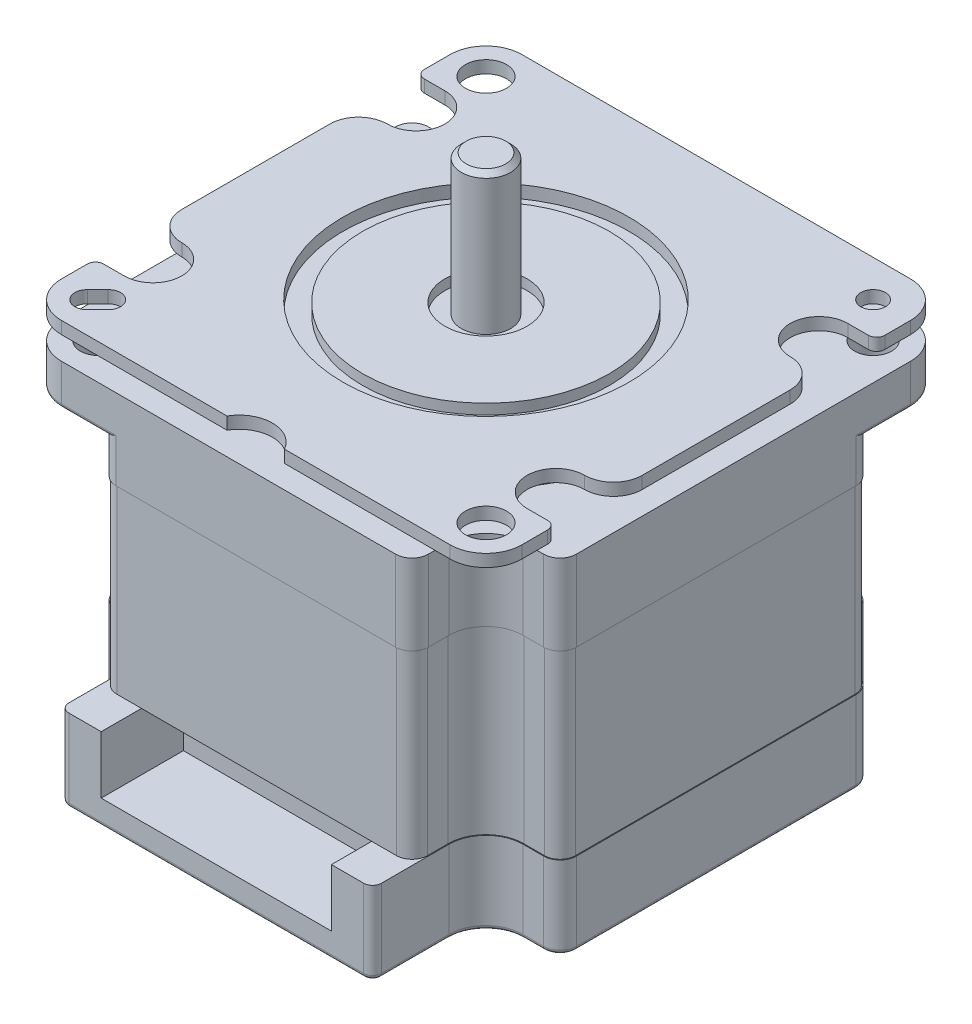
SolidWorks part; units mm, degrees
ref_plane "Front Plane" through (0, 0, 0) normal (0, 0, 1) x (1, 0, 0)
ref_plane "Top Plane" through (0, 0, 0) normal (0, 1, 0) x (1, 0, 0)
ref_plane "Right Plane" through (0, 0, 0) normal (1, 0, 0) x (0, 0, -1)
sketch "Sketch1" plane through (0, 0, 0) normal (0, 1, 0) x (1, 0, 0)
  line L0 (-24.2471, -24.2471) -> (-22.9743, -22.9743) construction
  line L1 (-23.6365, -28) -> (-3.5, -28)
  line L2 (-28, -23.6365) -> (-28, -20.5)
  line L3 (-23.6365, 28) -> (23.6365, 28)
  line L4 (28, -23.6365) -> (28, -20.5)
  line L5 (-26.722, -26.722) -> (26.722, 26.722) construction
  line L6 (-28, 28) -> (28, -28) construction
  line L7 (-25.3077, -23.1864) -> (-24.035, -21.9136)
  line L8 (-23.1864, -25.3077) -> (-21.9136, -24.035)
  line L9 (0, 0) -> (28, 0) construction
  line L10 (24.5002, 19.5) -> (27, 19.5)
  line L11 (24.5002, -19.5) -> (27, -19.5)
  line L12 (28, 20.5) -> (28, 23.6365)
  line L13 (28, -9.0002) -> (28, 9.0002)
  line L14 (0, 0) -> (0, 28) construction
  line L15 (-24.5002, -19.5) -> (-27, -19.5)
  line L16 (-24.5002, 19.5) -> (-27, 19.5)
  line L17 (-28, 20.5) -> (-28, 23.6365)
  line L18 (-28, -9.0002) -> (-28, 9.0002)
  line L19 (0, -28) -> (0, -26) construction
  line L21 (3.5, -28) -> (23.6365, -28)
  circle A0 centre (-23.5113, 23.5113) radius 2.5
  circle A1 centre (23.5113, -23.5113) radius 2.5
  arc A2 (-28, -23.6365) -> (-23.6365, -28) centre (-23.6365, -23.6365) ccw
  arc A3 (23.6365, -28) -> (28, -23.6365) centre (23.6365, -23.6365) ccw
  arc A4 (28, 23.6365) -> (23.6365, 28) centre (23.6365, 23.6365) ccw
  arc A5 (-23.6365, 28) -> (-28, 23.6365) centre (-23.6365, 23.6365) ccw
  circle A6 centre (23.54, 23.54) radius 1.5
  arc A7 (-25.3077, -23.1864) -> (-23.1864, -25.3077) centre (-24.2471, -24.2471) ccw
  arc A8 (-21.9136, -24.035) -> (-24.035, -21.9136) centre (-22.9743, -22.9743) ccw
  circle A9 centre (0, 0) radius 17.4
  arc A10 (24.5002, 19.5) -> (24.5002, 12.5) centre (24.5002, 16) ccw
  arc A11 (27, 19.5) -> (28, 20.5) centre (27, 20.5) ccw
  arc A12 (24.5002, 12.5) -> (28, 9.0002) centre (24.5002, 9.0002) cw
  arc A13 (24.5002, -12.5) -> (28, -9.0002) centre (24.5002, -9.0002) ccw
  arc A14 (24.5002, -19.5) -> (24.5002, -12.5) centre (24.5002, -16) cw
  arc A15 (27, -19.5) -> (28, -20.5) centre (27, -20.5) cw
  arc A16 (-27, -19.5) -> (-28, -20.5) centre (-27, -20.5) ccw
  arc A17 (-24.5002, -19.5) -> (-24.5002, -12.5) centre (-24.5002, -16) ccw
  arc A18 (-24.5002, -12.5) -> (-28, -9.0002) centre (-24.5002, -9.0002) cw
  arc A19 (-24.5002, 12.5) -> (-28, 9.0002) centre (-24.5002, 9.0002) ccw
  arc A20 (-24.5002, 19.5) -> (-24.5002, 12.5) centre (-24.5002, 16) cw
  arc A21 (-27, 19.5) -> (-28, 20.5) centre (-27, 20.5) cw
  arc A22 (-3.5, -28) -> (3.5, -28) centre (0, -30.017) cw
  point P0 (0, 0)
  point P26 (-23.6107, -23.6107)
  point P36 (28, 19.5)
  point P70 (3.5, -28)
  dimension "D2" = 5
  dimension "D3" = 66.5
  dimension "D4" = 4.3635
  dimension "D5" = 3
  dimension "D6" = 4.5
  dimension "D7" = 1.5
  dimension "D8" = 1.8
  dimension "D9" = 34.8
  dimension "D10" = 1
  dimension "D11" = 2
  dimension "D1" = 3.5
  dimension "D12" = 3.5
extrude "Boss-Extrude1" add sketch "Sketch1" along normal blind 1.5
ref_plane "Plane1" through (0, -2.8, 0) normal (0, -1, 0) x (-1, 0, 0)
sketch "Sketch2" plane through (0, -2.8, 0) normal (0, -1, 0) x (-1, 0, 0)
  line L0 (19, 26) -> (19, 23.5)
  line L1 (23.6365, -28) -> (-17, -28)
  line L2 (28, -23.6365) -> (28, 17)
  line L3 (17, 28) -> (-23.6365, 28)
  line L4 (-28, -17) -> (-28, 23.6365)
  line L5 (26.722, -26.722) -> (-26.722, 26.722) construction
  line L6 (20.318, 20.318) -> (-20.318, -20.318) construction
  line L7 (23.5, 19) -> (26, 19)
  line L8 (-19, -23.5) -> (-19, -26)
  line L9 (-26, -19) -> (-23.5, -19)
  arc A0 (-23.6365, 28) -> (-28, 23.6365) centre (-23.6365, 23.6365) ccw construction
  arc A1 (-23.6365, 28) -> (-28, 23.6365) centre (-23.6365, 23.6365) ccw
  arc A2 (23.5, 19) -> (19, 23.5) centre (23.5, 23.5) cw
  arc A3 (28, 17) -> (26, 19) centre (26, 17) ccw
  arc A4 (19, 26) -> (17, 28) centre (17, 26) ccw
  arc A5 (28, -23.6365) -> (23.6365, -28) centre (23.6365, -23.6365) cw
  arc A6 (-17, -28) -> (-19, -26) centre (-17, -26) cw
  arc A7 (-19, -23.5) -> (-23.5, -19) centre (-23.5, -23.5) ccw
  arc A8 (-26, -19) -> (-28, -17) centre (-26, -17) cw
  circle A9 centre (-23.54, 23.54) radius 1.5 construction
  circle A10 centre (-23.54, 23.54) radius 1.5 construction
  circle A11 centre (-23.54, 23.54) radius 2.25
  circle A12 centre (23.54, -23.54) radius 2.25
  point P0 (0, 0)
  dimension "D2" = 4.3635
  dimension "D4" = 4.5
  dimension "D5" = 2
  dimension "D7" = 4.5
  dimension "D1" = 9
  dimension "D3" = 9
extrude "Boss-Extrude2" add sketch "Sketch2" along normal blind 5 separate body
sketch "Sketch3" plane through (0, -7.8, 0) normal (0, -1, 0) x (1, 0, 0)
  line L0 (0, 0) -> (-28, 0) construction
  line L1 (-28, 0) -> (0, 0) construction
  line L2 (0, 0) -> (0, -28) construction
  line L3 (19, -23.5) -> (19, -26)
  line L4 (26, -19) -> (23.5, -19)
  line L5 (-19, 23.5) -> (-19, 26)
  line L6 (-26, 19) -> (-23.5, 19)
  line L8 (-26, -19) -> (-23.5, -19)
  line L9 (-19, -23.5) -> (-19, -26)
  line L10 (-17, -28) -> (23.6365, -28)
  line L11 (28, -23.6365) -> (28, 17)
  line L12 (26, 19) -> (23.5, 19)
  line L13 (19, 23.5) -> (19, 26)
  line L14 (17, 28) -> (-23.6365, 28)
  line L15 (-28, 23.6365) -> (-28, -17)
  line L16 (-26, -19) -> (-23.5, -19)
  line L17 (-19, -23.5) -> (-19, -26)
  line L18 (-17, -28) -> (23.6365, -28)
  line L19 (28, -23.6365) -> (28, 17)
  line L20 (26, 19) -> (23.5, 19)
  line L21 (19, 23.5) -> (19, 26)
  line L22 (17, 28) -> (-23.6365, 28)
  line L23 (-28, 23.6365) -> (-28, -17)
  arc A0 (19, -26) -> (17, -28) centre (17, -26) cw
  arc A1 (19, -23.5) -> (23.5, -19) centre (23.5, -23.5) cw
  arc A2 (28, -17) -> (26, -19) centre (26, -17) cw
  arc A3 (-19, 26) -> (-17, 28) centre (-17, 26) cw
  arc A4 (-19, 23.5) -> (-23.5, 19) centre (-23.5, 23.5) cw
  arc A5 (-28, 17) -> (-26, 19) centre (-26, 17) cw
  arc A8 (-28, -17) -> (-26, -19) centre (-26, -17) ccw
  arc A9 (-19, -23.5) -> (-23.5, -19) centre (-23.5, -23.5) ccw
  arc A10 (-19, -26) -> (-17, -28) centre (-17, -26) ccw
  arc A11 (23.6365, -28) -> (28, -23.6365) centre (23.6365, -23.6365) ccw
  arc A12 (28, 17) -> (26, 19) centre (26, 17) ccw
  arc A13 (19, 23.5) -> (23.5, 19) centre (23.5, 23.5) ccw
  arc A14 (19, 26) -> (17, 28) centre (17, 26) ccw
  arc A15 (-23.6365, 28) -> (-28, 23.6365) centre (-23.6365, 23.6365) ccw
  arc A16 (-28, -17) -> (-26, -19) centre (-26, -17) ccw
  arc A17 (-19, -23.5) -> (-23.5, -19) centre (-23.5, -23.5) ccw
  arc A18 (-19, -26) -> (-17, -28) centre (-17, -26) ccw
  arc A19 (23.6365, -28) -> (28, -23.6365) centre (23.6365, -23.6365) ccw
  arc A20 (28, 17) -> (26, 19) centre (26, 17) ccw
  arc A21 (19, 23.5) -> (23.5, 19) centre (23.5, 23.5) ccw
  arc A22 (19, 26) -> (17, 28) centre (17, 26) ccw
  arc A23 (-23.6365, 28) -> (-28, 23.6365) centre (-23.6365, 23.6365) ccw
  arc M18 (-28, -17) -> (-26, -19) centre (-26, -17) ccw
  line M19 (-26, -19) -> (-23.5, -19)
  arc M20 (-23.5, -19) -> (-19, -23.5) centre (-23.5, -23.5) cw
  line M21 (-19, -23.5) -> (-19, -26)
  arc M22 (-19, -26) -> (-17, -28) centre (-17, -26) ccw
  line M23 (-17, -28) -> (23.6365, -28)
  arc M26 (28, 17) -> (26, 19) centre (26, 17) ccw
  line M27 (26, 19) -> (23.5, 19)
  arc M28 (23.5, 19) -> (19, 23.5) centre (23.5, 23.5) cw
  line M29 (19, 23.5) -> (19, 26)
  arc M30 (19, 26) -> (17, 28) centre (17, 26) ccw
  line M31 (17, 28) -> (-23.6365, 28)
  dimension "D1" = 0
extrude "Boss-Extrude3" add sketch "Sketch3" along normal blind 4.8 contours A5 L23 A0 L3 A1 L4 A2 L19 A3 L5 A4 L6 M18 M19 M20 M21 M22 M23 M26 M27 M28 M29 M30 M31
sketch "Sketch4" plane through (0, -12.6, 0) normal (0, -1, 0) x (1, 0, 0)
  line L0 (27.9, -17) -> (27.9, 17)
  line L1 (26, 18.9) -> (23.5, 18.9)
  line L2 (18.9, 23.5) -> (18.9, 26)
  line L3 (17, 27.9) -> (-17, 27.9)
  line L4 (-18.9, 26) -> (-18.9, 23.5)
  line L5 (-23.5, 18.9) -> (-26, 18.9)
  line L6 (-27.9, 17) -> (-27.9, -17)
  line L7 (-26, -18.9) -> (-23.5, -18.9)
  line L8 (-18.9, -23.5) -> (-18.9, -26)
  line L9 (-17, -27.9) -> (17, -27.9)
  line L10 (18.9, -26) -> (18.9, -23.5)
  line L11 (23.5, -18.9) -> (26, -18.9)
  line L12 (-28, 17) -> (-28, -17)
  line L13 (-26, -19) -> (-23.5, -19)
  line L14 (-19, -23.5) -> (-19, -26)
  line L15 (-17, -28) -> (17, -28)
  line L16 (19, -26) -> (19, -23.5)
  line L17 (23.5, -19) -> (26, -19)
  line L18 (28, -17) -> (28, 17)
  line L19 (26, 19) -> (23.5, 19)
  line L20 (19, 23.5) -> (19, 26)
  line L21 (17, 28) -> (-17, 28)
  line L22 (-19, 26) -> (-19, 23.5)
  line L23 (-23.5, 19) -> (-26, 19)
  line L24 (-28, 17) -> (-28, -17)
  line L25 (-26, -19) -> (-23.5, -19)
  line L26 (-19, -23.5) -> (-19, -26)
  line L27 (-17, -28) -> (17, -28)
  line L28 (19, -26) -> (19, -23.5)
  line L29 (23.5, -19) -> (26, -19)
  line L30 (28, -17) -> (28, 17)
  line L31 (26, 19) -> (23.5, 19)
  line L32 (19, 23.5) -> (19, 26)
  line L33 (17, 28) -> (-17, 28)
  line L34 (-19, 26) -> (-19, 23.5)
  line L35 (-23.5, 19) -> (-26, 19)
  arc A0 (27.9, 17) -> (26, 18.9) centre (26, 17) ccw
  arc A1 (18.9, 23.5) -> (23.5, 18.9) centre (23.5, 23.5) ccw
  arc A2 (18.9, 26) -> (17, 27.9) centre (17, 26) ccw
  arc A3 (-17, 27.9) -> (-18.9, 26) centre (-17, 26) ccw
  arc A4 (-23.5, 18.9) -> (-18.9, 23.5) centre (-23.5, 23.5) ccw
  arc A5 (-26, 18.9) -> (-27.9, 17) centre (-26, 17) ccw
  arc A6 (-27.9, -17) -> (-26, -18.9) centre (-26, -17) ccw
  arc A7 (-18.9, -23.5) -> (-23.5, -18.9) centre (-23.5, -23.5) ccw
  arc A8 (-18.9, -26) -> (-17, -27.9) centre (-17, -26) ccw
  arc A9 (17, -27.9) -> (18.9, -26) centre (17, -26) ccw
  arc A10 (23.5, -18.9) -> (18.9, -23.5) centre (23.5, -23.5) ccw
  arc A11 (26, -18.9) -> (27.9, -17) centre (26, -17) ccw
  arc A12 (-26, 19) -> (-28, 17) centre (-26, 17) ccw
  arc A13 (-28, -17) -> (-26, -19) centre (-26, -17) ccw
  arc A14 (-19, -23.5) -> (-23.5, -19) centre (-23.5, -23.5) ccw
  arc A15 (-19, -26) -> (-17, -28) centre (-17, -26) ccw
  arc A16 (17, -28) -> (19, -26) centre (17, -26) ccw
  arc A17 (23.5, -19) -> (19, -23.5) centre (23.5, -23.5) ccw
  arc A18 (26, -19) -> (28, -17) centre (26, -17) ccw
  arc A19 (28, 17) -> (26, 19) centre (26, 17) ccw
  arc A20 (19, 23.5) -> (23.5, 19) centre (23.5, 23.5) ccw
  arc A21 (19, 26) -> (17, 28) centre (17, 26) ccw
  arc A22 (-17, 28) -> (-19, 26) centre (-17, 26) ccw
  arc A23 (-23.5, 19) -> (-19, 23.5) centre (-23.5, 23.5) ccw
  arc A24 (-26, 19) -> (-28, 17) centre (-26, 17) ccw
  arc A25 (-28, -17) -> (-26, -19) centre (-26, -17) ccw
  arc A26 (-19, -23.5) -> (-23.5, -19) centre (-23.5, -23.5) ccw
  arc A27 (-19, -26) -> (-17, -28) centre (-17, -26) ccw
  arc A28 (17, -28) -> (19, -26) centre (17, -26) ccw
  arc A29 (23.5, -19) -> (19, -23.5) centre (23.5, -23.5) ccw
  arc A30 (26, -19) -> (28, -17) centre (26, -17) ccw
  arc A31 (28, 17) -> (26, 19) centre (26, 17) ccw
  arc A32 (19, 23.5) -> (23.5, 19) centre (23.5, 23.5) ccw
  arc A33 (19, 26) -> (17, 28) centre (17, 26) ccw
  arc A34 (-17, 28) -> (-19, 26) centre (-17, 26) ccw
  arc A35 (-23.5, 19) -> (-19, 23.5) centre (-23.5, 23.5) ccw
  dimension "D1" = 0
  dimension "D2" = 0.1
extrude "Boss-Extrude4" add sketch "Sketch4" along normal blind 22 contours L11 A11 L0 A0 L1 A1 L2 A2 L3 A3 L4 A4 L5 A5 L6 A6 L7 A7 L8 A8 L9 A9 L10 A10
sketch "Sketch5" plane through (0, -34.6, 0) normal (0, -1, 0) x (1, 0, 0)
  line L0 (-17.93, 32.7) -> (17.93, 32.7)
  line L1 (28, -17) -> (28, 17)
  line L2 (26, 19) -> (23.5, 19)
  line L3 (19, 23.5) -> (19, 31.73)
  line L4 (-17.93, 32.8) -> (17.93, 32.8)
  line L5 (-19, 31.73) -> (-19, 23.5)
  line L6 (-23.5, 19) -> (-26, 19)
  line L7 (-28, 17) -> (-28, -17)
  line L8 (-26, -19) -> (-23.5, -19)
  line L9 (-19, -23.5) -> (-19, -26)
  line L10 (-17, -28) -> (17, -28)
  line L11 (19, -26) -> (19, -23.5)
  line L12 (23.5, -18.9) -> (26, -18.9)
  line L13 (27.9, -17) -> (27.9, 17)
  line L14 (26, 18.9) -> (23.5, 18.9)
  line L15 (18.9, 23.5) -> (18.9, 26)
  line L16 (17, 27.9) -> (-17, 27.9)
  line L17 (-18.9, 26) -> (-18.9, 23.5)
  line L18 (-23.5, 18.9) -> (-26, 18.9)
  line L19 (-27.9, 17) -> (-27.9, -17)
  line L20 (-26, -18.9) -> (-23.5, -18.9)
  line L21 (-18.9, -23.5) -> (-18.9, -26)
  line L22 (-17, -27.9) -> (17, -27.9)
  line L23 (18.9, -26) -> (18.9, -23.5)
  line L24 (23.5, -18.9) -> (26, -18.9)
  line L25 (27.9, -17) -> (27.9, 17)
  line L26 (26, 18.9) -> (23.5, 18.9)
  line L27 (18.9, 23.5) -> (18.9, 31.73)
  line L28 (23.5, -19) -> (26, -19)
  line L29 (-18.9, 31.73) -> (-18.9, 23.5)
  line L30 (-23.5, 18.9) -> (-26, 18.9)
  line L31 (-27.9, 17) -> (-27.9, -17)
  line L32 (-26, -18.9) -> (-23.5, -18.9)
  line L33 (-18.9, -23.5) -> (-18.9, -26)
  line L34 (-17, -27.9) -> (17, -27.9)
  line L35 (18.9, -26) -> (18.9, -23.5)
  line L36 (-28, 17) -> (-28, -17)
  line L37 (-26, -19) -> (-23.5, -19)
  line L38 (-19, -23.5) -> (-19, -26)
  line L39 (-17, -28) -> (17, -28)
  line L40 (19, -26) -> (19, -23.5)
  line L41 (23.5, -19) -> (26, -19)
  line L42 (28, -17) -> (28, 17)
  line L43 (26, 19) -> (23.5, 19)
  line L44 (19, 23.5) -> (19, 26)
  line L45 (17, 28) -> (-17, 28)
  line L46 (-19, 26) -> (-19, 23.5)
  line L47 (-23.5, 19) -> (-26, 19)
  line L48 (-28, 17) -> (-28, -17)
  line L49 (-26, -19) -> (-23.5, -19)
  line L50 (-19, -23.5) -> (-19, -26)
  line L51 (-17, -28) -> (17, -28)
  line L52 (19, -26) -> (19, -23.5)
  line L53 (23.5, -19) -> (26, -19)
  line L54 (28, -17) -> (28, 17)
  line L55 (26, 19) -> (23.5, 19)
  line L56 (19, 23.5) -> (19, 26)
  line L58 (-19, 26) -> (-19, 23.5)
  line L59 (-23.5, 19) -> (-26, 19)
  arc A0 (18.9, 31.73) -> (17.93, 32.7) centre (17.93, 31.73) ccw
  arc A1 (-17.93, 32.7) -> (-18.9, 31.73) centre (-17.93, 31.73) ccw
  arc A2 (28, 17) -> (26, 19) centre (26, 17) ccw
  arc A3 (19, 23.5) -> (23.5, 19) centre (23.5, 23.5) ccw
  arc A4 (19, 31.73) -> (17.93, 32.8) centre (17.93, 31.73) ccw
  arc A5 (-17.93, 32.8) -> (-19, 31.73) centre (-17.93, 31.73) ccw
  arc A6 (-23.5, 19) -> (-19, 23.5) centre (-23.5, 23.5) ccw
  arc A7 (-26, 19) -> (-28, 17) centre (-26, 17) ccw
  arc A8 (-28, -17) -> (-26, -19) centre (-26, -17) ccw
  arc A9 (-19, -23.5) -> (-23.5, -19) centre (-23.5, -23.5) ccw
  arc A10 (-19, -26) -> (-17, -28) centre (-17, -26) ccw
  arc A11 (17, -28) -> (19, -26) centre (17, -26) ccw
  arc A12 (26, -18.9) -> (27.9, -17) centre (26, -17) ccw
  arc A13 (27.9, 17) -> (26, 18.9) centre (26, 17) ccw
  arc A14 (18.9, 23.5) -> (23.5, 18.9) centre (23.5, 23.5) ccw
  arc A15 (18.9, 26) -> (17, 27.9) centre (17, 26) ccw
  arc A16 (-17, 27.9) -> (-18.9, 26) centre (-17, 26) ccw
  arc A17 (-23.5, 18.9) -> (-18.9, 23.5) centre (-23.5, 23.5) ccw
  arc A18 (-26, 18.9) -> (-27.9, 17) centre (-26, 17) ccw
  arc A19 (-27.9, -17) -> (-26, -18.9) centre (-26, -17) ccw
  arc A20 (-18.9, -23.5) -> (-23.5, -18.9) centre (-23.5, -23.5) ccw
  arc A21 (-18.9, -26) -> (-17, -27.9) centre (-17, -26) ccw
  arc A22 (17, -27.9) -> (18.9, -26) centre (17, -26) ccw
  arc A23 (23.5, -18.9) -> (18.9, -23.5) centre (23.5, -23.5) ccw
  arc A24 (26, -18.9) -> (27.9, -17) centre (26, -17) ccw
  arc A25 (27.9, 17) -> (26, 18.9) centre (26, 17) ccw
  arc A26 (18.9, 23.5) -> (23.5, 18.9) centre (23.5, 23.5) ccw
  arc A27 (23.5, -19) -> (19, -23.5) centre (23.5, -23.5) ccw
  arc A28 (26, -19) -> (28, -17) centre (26, -17) ccw
  arc A29 (-23.5, 18.9) -> (-18.9, 23.5) centre (-23.5, 23.5) ccw
  arc A30 (-26, 18.9) -> (-27.9, 17) centre (-26, 17) ccw
  arc A31 (-27.9, -17) -> (-26, -18.9) centre (-26, -17) ccw
  arc A32 (-18.9, -23.5) -> (-23.5, -18.9) centre (-23.5, -23.5) ccw
  arc A33 (-18.9, -26) -> (-17, -27.9) centre (-17, -26) ccw
  arc A34 (17, -27.9) -> (18.9, -26) centre (17, -26) ccw
  arc A35 (23.5, -18.9) -> (18.9, -23.5) centre (23.5, -23.5) ccw
  arc A36 (-26, 19) -> (-28, 17) centre (-26, 17) ccw
  arc A37 (-28, -17) -> (-26, -19) centre (-26, -17) ccw
  arc A38 (-19, -23.5) -> (-23.5, -19) centre (-23.5, -23.5) ccw
  arc A39 (-19, -26) -> (-17, -28) centre (-17, -26) ccw
  arc A40 (17, -28) -> (19, -26) centre (17, -26) ccw
  arc A41 (23.5, -19) -> (19, -23.5) centre (23.5, -23.5) ccw
  arc A42 (26, -19) -> (28, -17) centre (26, -17) ccw
  arc A43 (28, 17) -> (26, 19) centre (26, 17) ccw
  arc A44 (19, 23.5) -> (23.5, 19) centre (23.5, 23.5) ccw
  arc A45 (19, 26) -> (17, 28) centre (17, 26) ccw
  arc A46 (-17, 28) -> (-19, 26) centre (-17, 26) ccw
  arc A47 (-23.5, 19) -> (-19, 23.5) centre (-23.5, 23.5) ccw
  arc A48 (-26, 19) -> (-28, 17) centre (-26, 17) ccw
  arc A49 (-28, -17) -> (-26, -19) centre (-26, -17) ccw
  arc A50 (-19, -23.5) -> (-23.5, -19) centre (-23.5, -23.5) ccw
  arc A51 (-19, -26) -> (-17, -28) centre (-17, -26) ccw
  arc A52 (17, -28) -> (19, -26) centre (17, -26) ccw
  arc A53 (23.5, -19) -> (19, -23.5) centre (23.5, -23.5) ccw
  arc A54 (26, -19) -> (28, -17) centre (26, -17) ccw
  arc A55 (28, 17) -> (26, 19) centre (26, 17) ccw
  arc A56 (19, 23.5) -> (23.5, 19) centre (23.5, 23.5) ccw
  arc A59 (-23.5, 19) -> (-19, 23.5) centre (-23.5, 23.5) ccw
  dimension "D3" = 0.97
  dimension "D5" = 60.8
  dimension "D1" = 0
  dimension "D2" = 0
  dimension "D4" = 0.1
extrude "Boss-Extrude6" add sketch "Sketch5" along normal blind 10 contours A4 L4 A5 L5 A6 L6 A7 L7 A8 L8 A9 L9 A10 L10 A11 L11 A27 L28 A28 L1 A2 L2 A3 L3
sketch "Sketch7" plane through (0, 0, 32.8) normal (0, 0, 1) x (1, 0, 0)
  line L0 (-17.93, -34.6) -> (17.93, -34.6) construction
  line L1 (-14, -41.6) -> (14, -41.6)
  line L2 (-14, -41.6) -> (-14, -34.6)
  line L3 (-14, -34.6) -> (14, -34.6)
  line L4 (14, -41.6) -> (14, -34.6)
  line L5 (-14, -41.6) -> (14, -34.6) construction
  line L6 (-14, -34.6) -> (14, -41.6) construction
  line L7 (0, 0) -> (0, -56.3906) construction
  point P0 (0, -38.1)
  dimension "D1" = 28
  dimension "D2" = 7
extrude "Cut-Extrude1" cut sketch "Sketch7" against normal blind 10
sketch "Sketch8" plane through (0, -2.8, 0) normal (0, 1, 0) x (1, 0, 0)
  circle A0 centre (0, 0) radius 22
  dimension "D1" = 44
extrude "Boss-Extrude7" add sketch "Sketch8" along normal blind 2.75
sketch "Sketch9" plane through (0, -0.05, 0) normal (0, 1, 0) x (1, 0, 0)
  circle A0 centre (0, 0) radius 15
  circle A1 centre (0, 0) radius 5
  dimension "D1" = 30
  dimension "D2" = 10
extrude "Boss-Extrude9" add sketch "Sketch9" along normal blind 1.25 contours A0 A1
sketch "Sketch10" plane through (0, -0.05, 0) normal (0, 1, 0) x (1, 0, 0)
  circle A0 centre (0, 0) radius 3
  dimension "D1" = 6
extrude "Boss-Extrude10" add sketch "Sketch10" along normal offset from surface (17.05 mm away) 15.5 separate body up to face at (-23.6107, 1.5, 23.6107) offset beyond the face yes
chamfer "Chamfer1" distance 0.6 angle 45 1 edges at (0, 17, 3)
sketch "Sketch11" plane through (0, -44.6, 0) normal (0, -1, 0) x (1, 0, 0)
  circle A0 centre (0, 0) radius 16.5
  circle A1 centre (0, 0) radius 14.1
  circle A2 centre (0, 0) radius 4.9
  dimension "D1" = 33
  dimension "D2" = 28.2
  dimension "D3" = 9.8
extrude "Cut-Extrude2" cut sketch "Sketch11" against normal blind 2.4 draft 5 contours A0 A1 | A2
fillet "Fillet1" radius 0.5 33 edges at (0, -44.6, -16.5) (-18.6866, -44.6, 32.4866) (-19, -44.6, 27.615) (-20.318, -44.6, 20.318) (-24.75, -44.6, 19) (-27.4142, -44.6, 18.4142) (-28, -44.6, 0) (-27.4142, -44.6, -18.4142) (-24.75, -44.6, -19) (-20.318, -44.6, -20.318) (-19, -44.6, -24.75) (-18.4142, -44.6, -27.4142) (0, -44.6, -28) (18.4142, -44.6, -27.4142) (19, -44.6, -24.75) (20.318, -44.6, -20.318) (24.75, -44.6, -19) (27.4142, -44.6, -18.4142) (28, -44.6, 0) (27.4142, -44.6, 18.4142) (24.75, -44.6, 19) (20.318, -44.6, 20.318) (19, -44.6, 27.615) (18.6866, -44.6, 32.4866) (0, -44.6, 32.8) (0, -44.6, -4.9) (0, -44.6, -14.1) (26.722, -7.8, -26.722) (-26.722, -7.8, 26.722)
sketch "Sketch12" plane through (0, -42.2, 0) normal (0, -1, 0) x (1, 0, 0)
  point P0 (0, 0)
sketch "Sketch13" plane through (0, 17, 0) normal (0, 1, 0) x (1, 0, 0)
  point P0 (0, 0)
